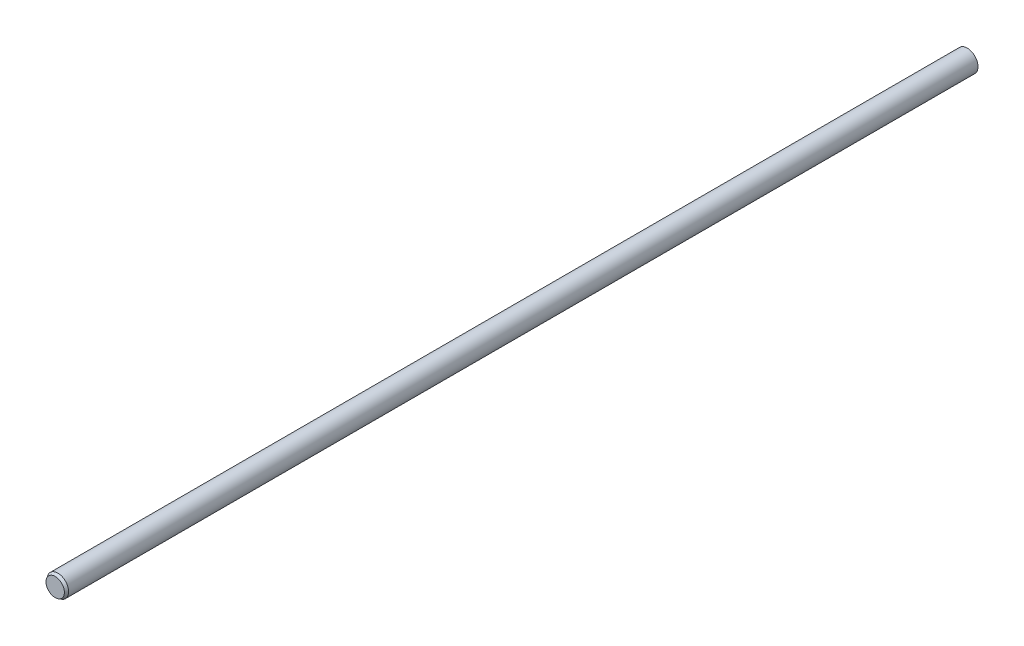
SolidWorks part; units mm, degrees
material "1060 Alloy"
ref_plane "Front Plane" through (0, 0, 0) normal (0, 0, 1) x (1, 0, 0)
ref_plane "Top Plane" through (0, 0, 0) normal (0, 1, 0) x (1, 0, 0)
ref_plane "Right Plane" through (0, 0, 0) normal (1, 0, 0) x (0, 0, -1)
sketch "Sketch1" plane through (0, 0, 0) normal (0, 0, 1) x (1, 0, 0)
  circle A0 centre (0, 0) radius 4
extrude "Boss-Extrude1" add sketch "Sketch1" along normal blind 340
chamfer "Chamfer1" distance 1 angle 30 2 edges at (4, 0, 340) (4, 0, 0)
